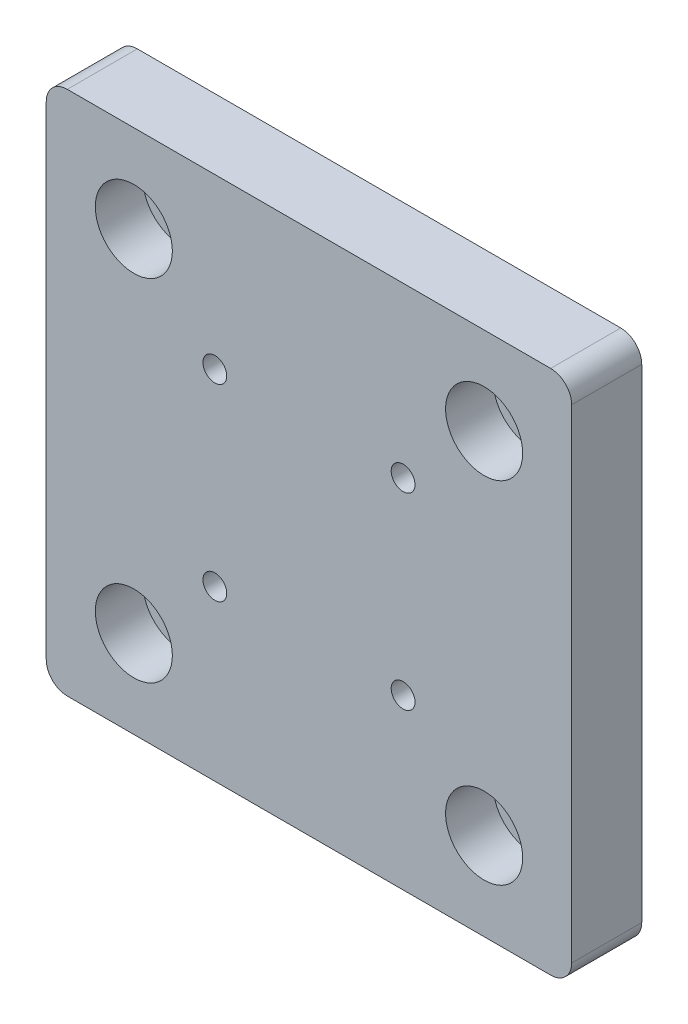
SolidWorks part; units mm, degrees
ref_plane "前视基准面" through (0, 0, 0) normal (0, 0, 1) x (1, 0, 0)
ref_plane "上视基准面" through (0, 0, 0) normal (0, 1, 0) x (1, 0, 0)
ref_plane "右视基准面" through (0, 0, 0) normal (1, 0, 0) x (0, 0, -1)
sketch "草图1" plane through (0, 0, 0) normal (0, 0, 1) x (1, 0, 0)
  line L1 (-37.5, 37.5) -> (37.5, 37.5)
  line L2 (-37.5, 37.5) -> (-37.5, -37.5)
  line L3 (-37.5, -37.5) -> (37.5, -37.5)
  line L4 (37.5, 37.5) -> (37.5, -37.5)
  line L5 (-37.5, 37.5) -> (37.5, -37.5) construction
  line L6 (-37.5, -37.5) -> (37.5, 37.5) construction
  point P0 (0, 0)
  point P6 (0, 0)
  dimension "D2" = 75
extrude "凸台-拉伸1" add sketch "草图1" along normal blind 10
sketch "草图5" plane through (0, 0, 10) normal (0, 0, 1) x (1, 0, 0)
  line L1 (25, 25) -> (-25, 25)
  line L2 (25, 25) -> (25, -25)
  line L3 (25, -25) -> (-25, -25)
  line L4 (-25, 25) -> (-25, -25)
  line L5 (25, 25) -> (-25, -25) construction
  line L6 (25, -25) -> (-25, 25) construction
  point P0 (0, 0)
  dimension "D1" = 50
hole_wizard "打孔尺寸(%根据)内六角圆柱头螺钉的类型1" positions "3D草图3" profile "草图6" counterbore size "M6" standard "GB"
sketch3d "3D草图3"
  point P0 (-25, 25, 10)
  point P3 (-25, -25, 10)
  point P6 (25, -25, 10)
  point P9 (25, 25, 10)
sketch "草图6" plane through (-25, 25, 10) normal (1, 0, 0) x (0, -1, 0)
  line L0 (0, 0) -> (0, 16.9828)
  line L1 (0, 16.9828) -> (3.3, 15)
  line L2 (3.3, 15) -> (3.3, 6.8)
  line L3 (3.3, 6.8) -> (5.5, 6.8)
  line L4 (5.5, 6.8) -> (5.5, 0)
  line L5 (5.5, 0) -> (0, 0)
  line L10 (0, 16.9828) -> (-3.3, 15) construction
  line L11 (0, -6.35) -> (0, 107.95) construction
  dimension "孔直径" = 6.6
  dimension "孔深度" = 15
  dimension "柱形沉头孔直径" = 11
  dimension "柱形沉头孔深度" = 6.8
  dimension "导头角度" = 118
fillet "圆角1" radius 3 4 edges at (37.5, -37.5, 5) (-37.5, -37.5, 5) (37.5, 37.5, 5) (-37.5, 37.5, 5)
sketch "草图8" plane through (0, 0, 0) normal (0, 0, -1) x (-1, 0, 0)
  line L1 (13.435, -13.435) -> (-13.435, -13.435)
  line L2 (13.435, -13.435) -> (13.435, 13.435)
  line L3 (13.435, 13.435) -> (-13.435, 13.435)
  line L4 (-13.435, -13.435) -> (-13.435, 13.435)
  line L5 (13.435, -13.435) -> (-13.435, 13.435) construction
  line L6 (13.435, 13.435) -> (-13.435, -13.435) construction
  point P0 (0, 0)
  dimension "D1" = 38
hole_wizard "打孔尺寸(%根据)内六角圆柱头螺钉的类型2" positions "草图9" profile "草图10" counterbore size "M3" standard "GB" end condition through all
sketch "草图9" plane through (0, 0, 0) normal (0, 0, -1) x (-1, 0, 0)
  point P0 (13.435, -13.435)
  point P3 (13.435, 13.435)
  point P6 (-13.435, 13.435)
  point P9 (-13.435, -13.435)
sketch "草图10" plane through (-13.435, -13.435, 0) normal (1, 0, 0) x (0, 1, 0)
  line L0 (0, 0) -> (0, 10)
  line L1 (0, 10) -> (1.7, 10)
  line L3 (1.7, 10) -> (1.7, 3.4)
  line L4 (1.7, 3.4) -> (3, 3.4)
  line L5 (3, 3.4) -> (3, 0)
  line L7 (3, 0) -> (0, 0)
  line L11 (0, -6.35) -> (0, 107.95) construction
  dimension "通孔孔直径" = 3.4
  dimension "通孔孔深度" = 10
  dimension "柱形沉头孔直径" = 6
  dimension "柱形沉头孔深度" = 3.4
